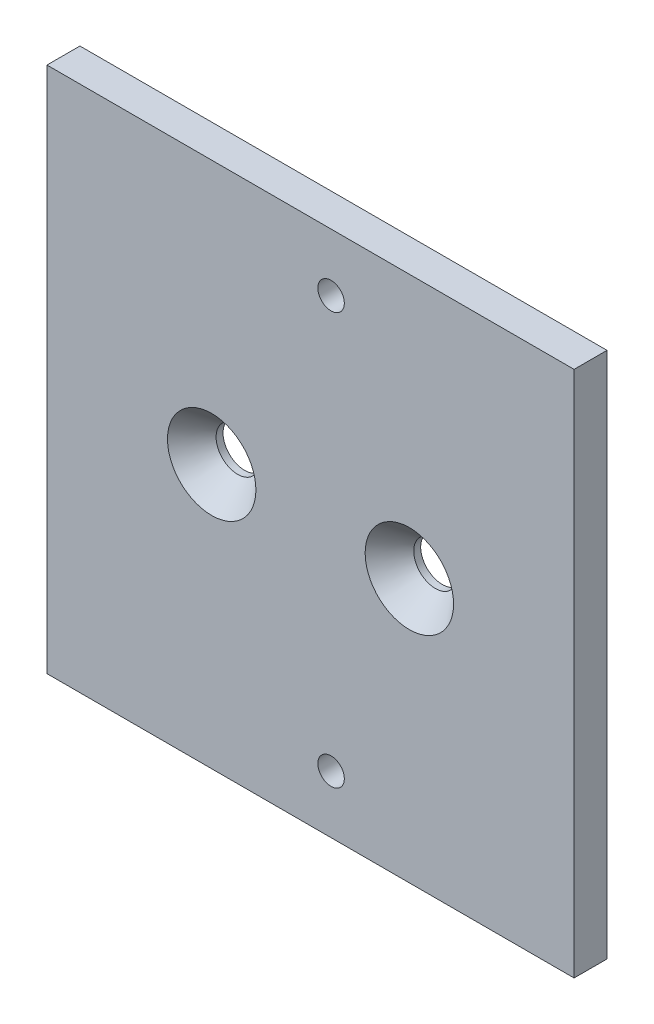
SolidWorks part; units mm, degrees
ref_plane "Front" through (0, 0, 0) normal (0, 0, 1) x (1, 0, 0)
ref_plane "Top" through (0, 0, 0) normal (0, 1, 0) x (1, 0, 0)
ref_plane "Right" through (0, 0, 0) normal (1, 0, 0) x (0, 0, -1)
sketch "Sketch1" plane through (0, 0, 0) normal (0, 0, 1) x (1, 0, 0)
  line L0 (-19.05, 0) -> (19.05, 0) construction
  line L1 (-50.8, 50.8) -> (50.8, 50.8)
  line L2 (-50.8, 50.8) -> (-50.8, -50.8)
  line L3 (-50.8, -50.8) -> (50.8, -50.8)
  line L4 (50.8, 50.8) -> (50.8, -50.8)
  line L5 (-50.8, 50.8) -> (50.8, -50.8) construction
  line L6 (-50.8, -50.8) -> (50.8, 50.8) construction
  circle A0 centre (-19.05, 0) radius 4.1656
  circle A1 centre (19.05, 0) radius 4.1656
  point P0 (0, 0)
  dimension "HoleDiameter" = 8.3312
  dimension "Width" = 101.6
  dimension "Height" = 101.6
  dimension "HoleSpacing" = 38.1
extrude "Boss-Extrude1" add sketch "Sketch1" along normal mid plane 6.35
sketch "Sketch2" plane through (0, 0, 0) normal (0, 1, 0) x (1, 0, 0)
  line L0 (-19.05, 3.175) -> (-19.05, -3.175) construction
  line L1 (-14.8844, 3.175) -> (-23.2156, 3.175) construction
  line L2 (-23.2156, -3.175) -> (-14.8844, -3.175) construction
  line L3 (-10.5283, -3.175) -> (-19.05, 6.6281)
  line L4 (-50.8, -3.175) -> (50.8, -3.175) construction
  line L5 (-19.05, 6.6281) -> (-19.05, -3.175)
  line L6 (-19.05, -3.175) -> (-10.5283, -3.175)
  line L7 (-19.05, 6.6281) -> (-27.5717, -3.175) construction
  dimension "CSinkDiameter" = 17.0434
  dimension "D2" = 82
revolve "Cut-Revolve1" cut sketch "Sketch2" angle 360 about L5
sketch "Sketch3" plane through (0, 0, 3.175) normal (0, 0, 1) x (1, 0, 0)
  point P0 (19.05, 0)
pattern_sketch "Sketch-Pattern1" of "Cut-Revolve1" driven by "Sketch3"
sketch "Sketch4" plane through (0, 0, 0) normal (1, 0, 0) x (0, 0, -1)
  line L0 (1.8361, 4.1656) -> (1.8361, -4.1656) construction
  line L1 (-3.175, 8.5217) -> (-3.175, -8.5217) construction
  line L2 (1.8361, 4.1656) -> (1.8361, -4.1656)
  line L3 (-3.175, 8.5217) -> (-3.175, -8.5217) construction
  line L4 (-3.175, 8.5217) -> (1.8361, 4.1656)
  line L5 (1.8361, 4.1656) -> (3.175, 4.1656)
  line L6 (3.175, -50.8) -> (3.175, 50.8) construction
  line L7 (-3.175, -8.5217) -> (1.8361, -4.1656)
  line L8 (1.8361, -4.1656) -> (3.175, -4.1656)
sketch "Sketch5" plane through (0, 0, 3.175) normal (0, 0, 1) x (1, 0, 0)
  point P0 (3.9624, -39.6875)
  point P1 (3.9624, 39.6875)
hole_wizard "1/4-20 Tapped Hole1" positions "Sketch6" profile "Sketch7" tap size "1/4-20" standard "ANSI Inch" end condition through all
sketch "Sketch6" plane through (0, 0, 3.175) normal (0, 0, 1) x (1, 0, 0)
  point P0 (3.9624, -39.6875)
  point P3 (3.9624, 39.6875)
sketch "Sketch7" plane through (3.9624, -39.6875, 3.175) normal (1, 0, 0) x (0, -1, 0)
  line L0 (0, 0) -> (0, 6.35)
  line L1 (0, 6.35) -> (2.5527, 6.35)
  line L2 (2.5527, 6.35) -> (2.5527, 0)
  line L5 (2.5527, 0) -> (0, 0)
  line L11 (0, -6.35) -> (0, 107.95) construction
  dimension "Thru Tap Drill Dia." = 5.1054
  dimension "Thru Tap Drill Depth" = 6.35
cosmetic thread "Hole Thread1" parameters "D2"=6.35
cosmetic thread "Hole Thread2" parameters "D2"=6.35
